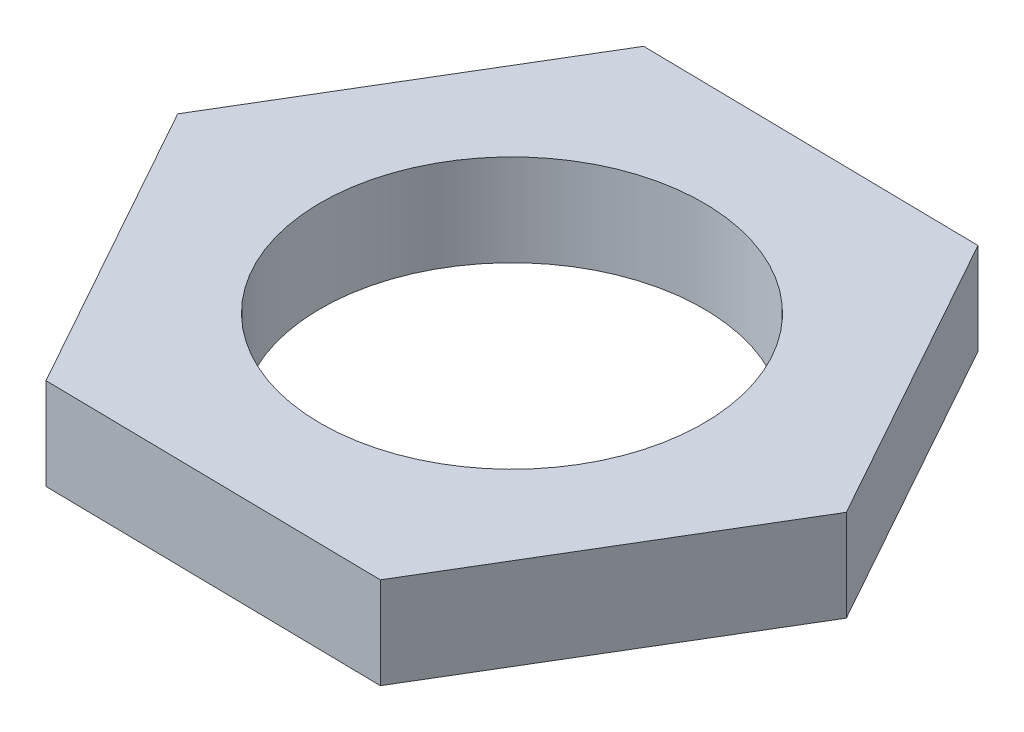
SolidWorks part; units mm, degrees
ref_plane "Front Plane" through (0, 0, 0) normal (0, 0, 1) x (1, 0, 0)
ref_plane "Top Plane" through (0, 0, 0) normal (0, 1, 0) x (1, 0, 0)
ref_plane "Right Plane" through (0, 0, 0) normal (1, 0, 0) x (0, 0, -1)
sketch "Sketch1" plane through (0, 0, 0) normal (0, 1, 0) x (1, 0, 0)
  line L1 (-4.3784, -7.3138) -> (4.1448, -7.4487)
  line L2 (4.1448, -7.4487) -> (8.5231, -0.1348)
  line L3 (8.5231, -0.1348) -> (4.3784, 7.3138)
  line L4 (4.3784, 7.3138) -> (-4.1448, 7.4487)
  line L5 (-4.1448, 7.4487) -> (-8.5231, 0.1348)
  line L6 (-8.5231, 0.1348) -> (-4.3784, -7.3138)
  circle A0 centre (0, 0) radius 7.3822 construction
  circle A1 centre (0, 0) radius 4.8
  dimension "D1" = 9.6
extrude "Boss-Extrude1" add sketch "Sketch1" along normal blind 2.3
thread "Thread1" pitch 1.0583 start angle 0, offset 0, length 0, pitch 1.0583, diameter 9.6
ref_plane "Plane1" through (-4.8, 2.3, 0) normal (0, 0, 1) x (-1, 0, 0)
sketch "Thread Profile1" plane through (-4.8, 2.3, 0) normal (0, 0, 1) x (-1, 0, 0)
  line L0 (0, 0) -> (0, 1.0583) construction
  line L11 (0, 0) -> (0, 0.926)
  line L12 (0, 0.926) -> (-0.5728, 0.5953)
  line L13 (-0.5728, 0.5953) -> (-0.5728, 0.3307)
  line L15 (-0.5728, 0.3307) -> (0, 0)
  line L17 (-0.5728, 0.463) -> (0, 0.463) construction
  point P2 (0, 0)
  dimension "Pitch" = 1.0583
  dimension "Profile_Angle" = 60
  dimension "Profile_Land" = 0.2646
  dimension "Profile_Height" = 0.5728
